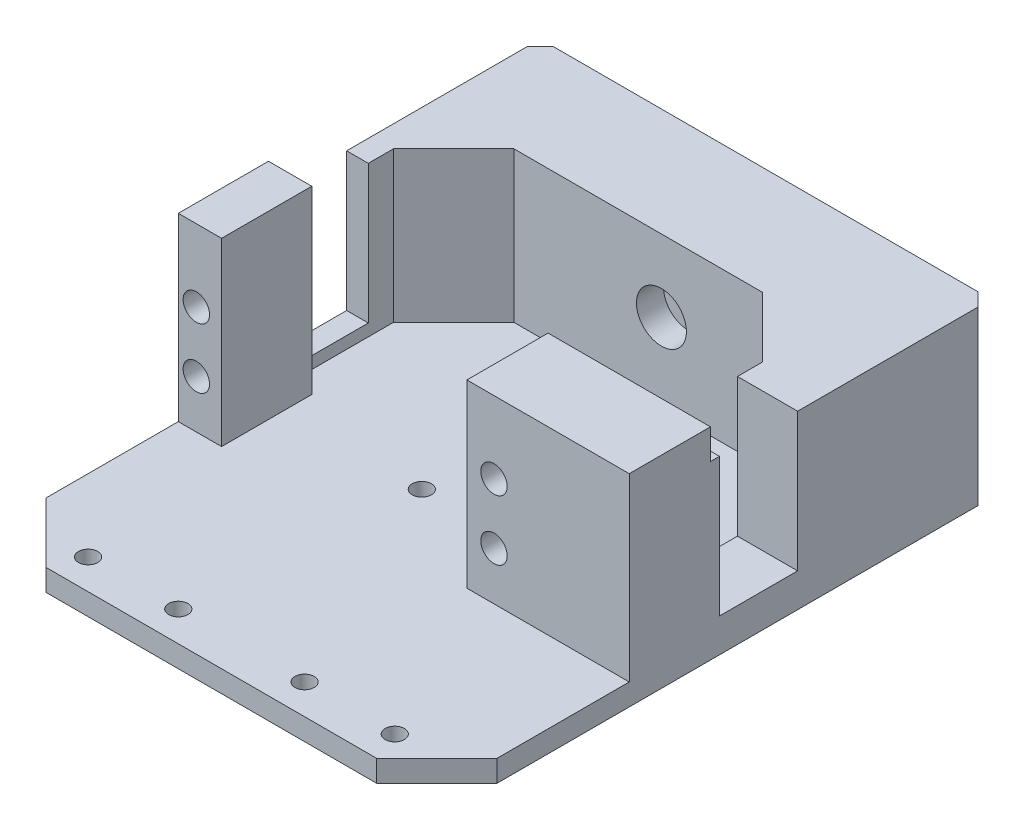
SolidWorks part; units mm, degrees
ref_plane "前视基准面" through (0, 0, 0) normal (0, 0, 1) x (1, 0, 0)
ref_plane "上视基准面" through (0, 0, 0) normal (0, 1, 0) x (1, 0, 0)
ref_plane "右视基准面" through (0, 0, 0) normal (1, 0, 0) x (0, 0, -1)
sketch "草图1" plane through (0, 0, 0) normal (0, 1, 0) x (1, 0, 0)
  line L1 (-37.5, -50) -> (37.5, -50)
  line L2 (-37.5, -50) -> (-37.5, 50)
  line L3 (-37.5, 50) -> (37.5, 50)
  line L4 (37.5, -50) -> (37.5, 50)
  line L5 (-37.5, -50) -> (37.5, 50) construction
  line L6 (-37.5, 50) -> (37.5, -50) construction
  point P0 (0, 0)
  dimension "D1" = 100
  dimension "D2" = 75
extrude "凸台-拉伸1" add sketch "草图1" along normal blind 3.6
chamfer "倒角1" distance 10 angle 45 4 edges at (-37.5, 1.8, -50) (37.5, 1.8, -50) (37.5, 1.8, 50) (-37.5, 1.8, 50)
sketch "草图2" plane through (0, 3.6, 0) normal (0, 1, 0) x (1, 0, 0)
  line L0 (37.5, -40) -> (37.5, 40) construction
  line L1 (-35.5, -18) -> (-30.3, -18)
  line L2 (-35.5, -18) -> (-35.5, -3)
  line L3 (-35.5, -3) -> (-30.3, -3)
  line L4 (-30.3, -18) -> (-30.3, -3)
  line L5 (-37.5, 40) -> (-37.5, -40) construction
  line L6 (25.5, -18) -> (10.5, -18)
  line L7 (25.5, -18) -> (25.5, -4.5)
  line L8 (25.5, -4.5) -> (10.5, -4.5)
  line L9 (10.5, -18) -> (10.5, -4.5)
  line L10 (-27.5, -50) -> (27.5, -50) construction
  dimension "D1" = 5.2
  dimension "D2" = 15
  dimension "D3" = 12
  dimension "D4" = 13.5
  dimension "D5" = 32
  dimension "D6" = 32
  dimension "D7" = 27
  dimension "D8" = 2
extrude "凸台-拉伸2" add sketch "草图2" along normal blind 30
sketch "草图3" plane through (-35.5, 0, 0) normal (-1, 0, 0) x (0, 0, 1)
  line L1 (3, 33.6) -> (18, 33.6)
  line L2 (3, 33.6) -> (3, 3.6)
  line L3 (3, 3.6) -> (18, 3.6)
  line L4 (18, 33.6) -> (18, 3.6)
extrude "凸台-拉伸3" add sketch "草图3" along normal up to surface (2 mm away) up to face at (-37.5, 1.8, 0)
sketch "草图4" plane through (25.5, 0, 0) normal (1, 0, 0) x (0, 0, -1)
  line L1 (-18, 33.6) -> (-4.5, 33.6)
  line L2 (-18, 33.6) -> (-18, 3.6)
  line L3 (-18, 3.6) -> (-4.5, 3.6)
  line L4 (-4.5, 33.6) -> (-4.5, 3.6)
extrude "凸台-拉伸4" add sketch "草图4" along normal up to surface (12 mm away) up to face at (37.5, 1.8, 0)
sketch "草图5" plane through (0, 0, 18) normal (0, 0, 1) x (1, 0, 0)
  line L0 (-37.5, 33.6) -> (-37.5, 3.6) construction
  circle A0 centre (-34.5, 21.6) radius 2.2
  circle A1 centre (-34.5, 11.6) radius 2.2
  circle A2 centre (15, 21.6) radius 2.2
  circle A3 centre (15, 11.6) radius 2.2
  dimension "D1" = 3
extrude "切除-拉伸1" cut sketch "草图5" against normal blind 115
sketch "草图6" plane through (0, 3.6, 0) normal (0, 1, 0) x (1, 0, 0)
  line L0 (37.5, -40) -> (37.5, -18) construction
  line L1 (-21.9, 24.2) -> (27.5, 24.2)
  line L2 (-21.9, 24.2) -> (-21.9, 42.2)
  line L3 (-21.9, 42.2) -> (27.5, 42.2)
  line L4 (27.5, 24.2) -> (27.5, 42.2)
  line L5 (-21.9, 24.2) -> (27.5, 42.2) construction
  line L6 (-21.9, 42.2) -> (27.5, 24.2) construction
  line L7 (27.5, 50) -> (-27.5, 50) construction
  point P0 (2.8, 33.2)
  dimension "D1" = 34.7
  dimension "D2" = 18
  dimension "D3" = 7.8
  dimension "D4" = 10
extrude "凸台-拉伸5" add sketch "草图6" along normal blind 25
sketch "草图7" plane through (0, 0, -42.2) normal (0, 0, -1) x (-1, 0, 0)
  line L0 (-27.5, 16.1) -> (21.9, 16.1) construction
  line L1 (-27.5, 28.6) -> (-27.5, 3.6) construction
  line L2 (21.9, 28.6) -> (21.9, 3.6) construction
  circle A0 centre (-2.8, 16.1) radius 1.6
  dimension "D1" = 3.2
sketch "草图8" plane through (0, 0, -24.2) normal (0, 0, 1) x (1, 0, 0)
  line L0 (-21.9, 28.6) -> (-21.9, 3.6) construction
  circle A0 centre (0.65, 16.6) radius 1.665
  dimension "D1" = 3.33
  dimension "D2" = 22.55
extrude "切除-拉伸3" cut sketch "草图8" against normal blind 25
sketch "草图9" plane through (0, 3.6, 0) normal (0, 1, 0) x (1, 0, 0)
  line L0 (-21.9, 42.2) -> (-37.5, 42.2)
  line L1 (-37.5, 40) -> (-37.5, -3) construction
  line L2 (-37.5, 42.2) -> (-37.5, -3)
  line L3 (-37.5, -3) -> (-33.9, -3)
  line L4 (-30.3, -3) -> (-37.5, -3) construction
  line L5 (-21.9, 42.2) -> (-21.9, 24.2)
  line L6 (-21.9, 24.2) -> (-33.9, 24.2)
  line L7 (-33.9, 24.2) -> (-33.9, -3)
  line L8 (37.5, -4.5) -> (37.5, 42.2)
  line L9 (37.5, 42.2) -> (27.5, 42.2)
  line L13 (37.5, -4.5) -> (10.5, -4.5) construction
  line L14 (27.5, -4.5) -> (37.5, -4.5)
  line L15 (27.5, 42.2) -> (27.5, 24.2)
  line L16 (27.5, 24.2) -> (27.5, -4.5)
extrude "凸台-拉伸7" add sketch "草图9" along normal up to surface (25 mm away) up to face at (2.8, 28.6, -33.2)
sketch "草图10" plane through (0, 3.6, 0) normal (0, 1, 0) x (1, 0, 0)
  line L0 (0, -18.48) -> (0, 18.48) construction
  line L1 (-18.48, 0) -> (18.48, 0) construction
  circle A0 centre (-7.5, 7.5) radius 1.6
  circle A1 centre (7.5, 7.5) radius 1.6
  circle A2 centre (7.5, -7.5) radius 1.6
  circle A3 centre (-7.5, -7.5) radius 1.6
  dimension "D1" = 3.2
  dimension "D2" = 15
  dimension "D3" = 15
extrude "切除-拉伸4" cut sketch "草图10" against normal blind 130
sketch "草图11" plane through (0, 28.6, 0) normal (0, 1, 0) x (1, 0, 0)
  line L0 (37.5, -18) -> (37.5, -40) construction
  line L1 (27.5, -4.5) -> (37.5, -4.5)
  line L2 (27.5, -4.5) -> (27.5, -16.5)
  line L3 (27.5, -16.5) -> (37.5, -16.5)
  line L4 (37.5, -4.5) -> (37.5, -16.5)
  dimension "D1" = 12
sketch "草图12" plane through (0, 3.6, 0) normal (0, 1, 0) x (1, 0, 0)
  line L0 (-37.5, -18) -> (-37.5, -40) construction
  line L1 (27.5, 50) -> (-27.5, 50) construction
  line L2 (0, -18.48) -> (0, 18.48) construction
  line L3 (-18.48, 0) -> (18.48, 0) construction
  circle A0 centre (-25.5, 45) radius 1.6
  circle A1 centre (-10.5, 45) radius 1.6
  circle A2 centre (10.5, 45) radius 1.6
  circle A3 centre (25.5, 45) radius 1.6
  circle A4 centre (25.5, -45) radius 1.6
  circle A5 centre (10.5, -45) radius 1.6
  circle A6 centre (-10.5, -45) radius 1.6
  circle A7 centre (-25.5, -45) radius 1.6
  dimension "D1" = 15
  dimension "D2" = 3.2
  dimension "D3" = 3.2
  dimension "D4" = 12
  dimension "D5" = 5
extrude "切除-拉伸6" cut sketch "草图12" against normal blind 120
sketch "草图13" plane through (0, 3.6, 0) normal (0, 1, 0) x (1, 0, 0)
  line L0 (-34.5701, 28.0875) -> (-33.9, 10.1)
  line L1 (-33.9, 24.2) -> (-33.9, -3) construction
  line L2 (-33.9, 10.1) -> (27.5, 10.1)
  line L3 (27.5, -4.5) -> (27.5, 24.2) construction
  line L4 (27.5, 10.1) -> (27.5, 28.0875)
  line L5 (27.5, 28.0875) -> (-34.5701, 28.0875)
  line L6 (-28.78, 9.7) -> (-25.25, 9.7) construction
  dimension "D1" = 0.4
  dimension "D2" = 18
sketch "草图14" plane through (0, 0, -42.2) normal (0, 0, -1) x (-1, 0, 0)
  circle A0 centre (-15, 21.6) radius 2.2
  circle A1 centre (-15, 11.6) radius 2.2
  circle A2 centre (34.5, 21.6) radius 2.2
  circle A3 centre (34.5, 11.6) radius 2.2
chamfer "倒角2" distance 10 angle 45 2 edges at (27.5, 16.1, -24.2) (-33.9, 16.1, -24.2)
sketch "草图15" plane through (0, 28.6, 0) normal (0, 1, 0) x (1, 0, 0)
  line L0 (-37.5, -3) -> (-37.5, 42.2) construction
  line L1 (-33.9, -3) -> (-37.5, -3)
  line L2 (-33.9, -3) -> (-33.9, 10)
  line L3 (-33.9, 10) -> (-37.5, 10)
  line L4 (-37.5, -3) -> (-37.5, 10)
  dimension "D1" = 13
extrude "切除-拉伸8" cut sketch "草图15" against normal blind 23
sketch "草图16" plane through (0, 0, -24.2) normal (0, 0, 1) x (1, 0, 0)
  circle A0 centre (0.65, 16.6) radius 4.155
  dimension "D1" = 8.31
extrude "切除-拉伸9" cut sketch "草图16" against normal blind 4.5
sketch "草图17" plane through (27.5, 0, 0) normal (-1, 0, 0) x (0, 0, 1)
  line L1 (-10, 28.6) -> (3, 28.6)
  line L2 (-10, 28.6) -> (-10, 5.6)
  line L3 (-10, 5.6) -> (3, 5.6)
  line L4 (3, 28.6) -> (3, 5.6)
extrude "切除-拉伸10" cut sketch "草图17" against normal blind 23
sketch "草图18" plane through (0, 0, 0) normal (0, -1, 0) x (1, 0, 0)
  line L0 (-37.5, -40) -> (-35.3, -42.2)
  line L1 (-35.3, -42.2) -> (-37.5, -42.2)
  line L2 (-37.5, -42.2) -> (-37.5, -40)
  line L3 (0, -18.48) -> (0, 18.48) construction
  line L4 (37.5, -42.2) -> (37.5, -40)
  line L5 (35.3, -42.2) -> (37.5, -42.2)
  line L6 (37.5, -40) -> (35.3, -42.2)
extrude "切除-拉伸11" cut sketch "草图18" against normal blind 33
